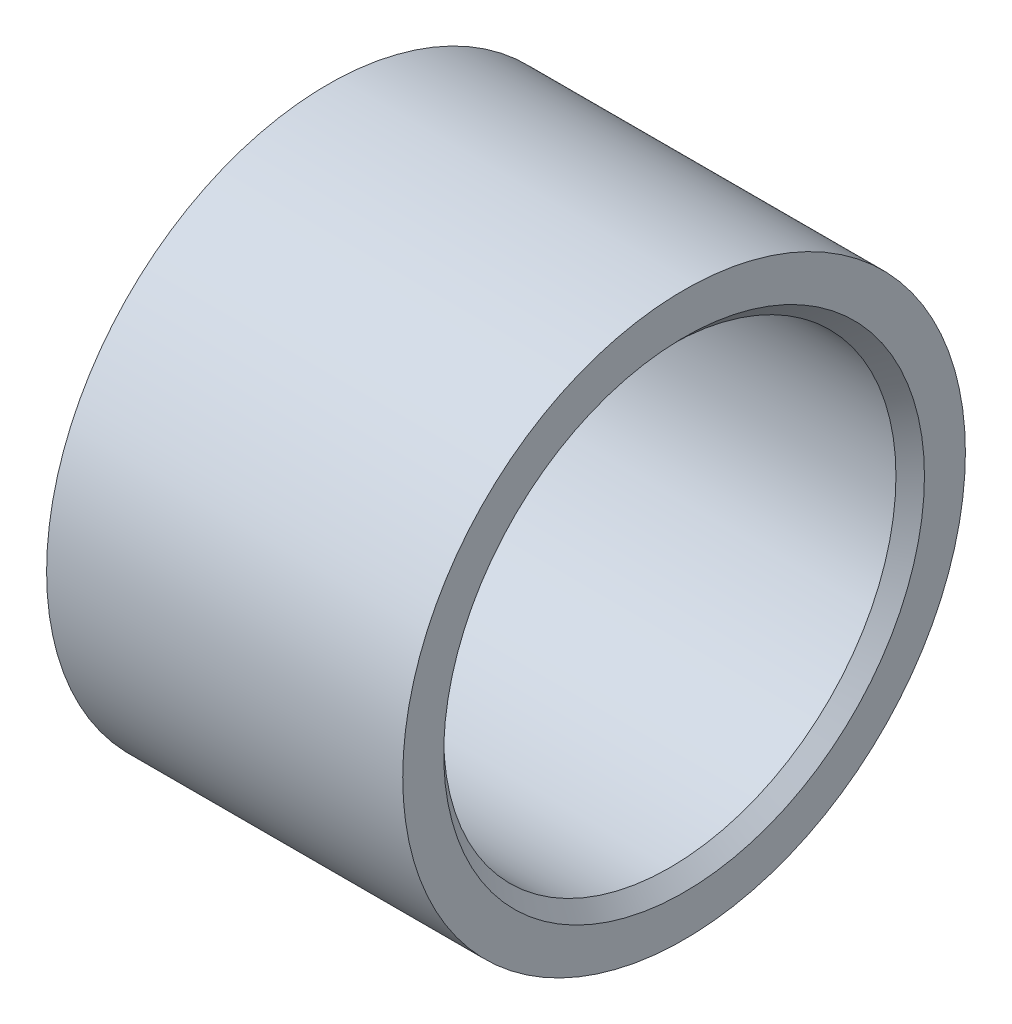
SolidWorks part; units mm, degrees
ref_plane "Front Plane" through (0, 0, 0) normal (0, 0, 1) x (1, 0, 0)
ref_plane "Top Plane" through (0, 0, 0) normal (0, 1, 0) x (1, 0, 0)
ref_plane "Right Plane" through (0, 0, 0) normal (1, 0, 0) x (0, 0, -1)
sketch "Sketch1" plane through (0, 0, 0) normal (1, 0, 0) x (0, 0, -1)
  circle A0 centre (-1400.1009, 313.5551) radius 10.033 construction
  circle A1 centre (-1400.1009, 313.5551) radius 8.0645 construction
  circle A2 centre (-1400.1009, 313.5551) radius 10.033
  circle A3 centre (-1400.1009, 313.5551) radius 8.0645
extrude "Boss-Extrude1" add sketch "Sketch1" along normal up to vertex (64.9161 mm away) from vertex at 52.2161
chamfer "Chamfer1" distance 0.508 angle 45 2 edges at (52.2161, 313.5551, 1392.0364) (64.9161, 313.5551, 1392.0364)
